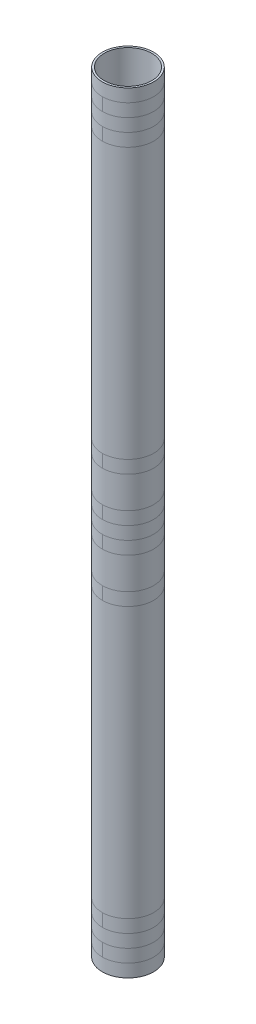
SolidWorks part; units mm, degrees
material "6063-O"
ref_plane "Front Plane" through (0, 0, 0) normal (0, 0, 1) x (1, 0, 0)
ref_plane "Top Plane" through (0, 0, 0) normal (0, 1, 0) x (1, 0, 0)
ref_plane "Right Plane" through (0, 0, 0) normal (1, 0, 0) x (0, 0, -1)
sketch "Sketch1" plane through (0, 0, 0) normal (0, 1, 0) x (1, 0, 0)
  circle A0 centre (0, 0) radius 20
  dimension "D1" = 30
extrude "Boss-Extrude1" add sketch "Sketch1" along normal blind 600
sketch "Sketch5" plane through (0, 600, 0) normal (0, 1, 0) x (1, 0, 0)
  circle A0 centre (0, 0) radius 18.5
  dimension "D1" = 24
extrude "Cut-Extrude1" cut sketch "Sketch5" against normal blind 600
ref_plane "Plane1" through (30, 0, 0) normal (1, 0, 0) x (0, 0, -1)
sketch "Sketch6" plane through (30, 0, 0) normal (1, 0, 0) x (0, 0, -1)
  line L0 (-20, 0) -> (20, 0) construction
  line L1 (-20, 600) -> (-20, 0) construction
  circle A0 centre (-5, 279.5) radius 2.5
  circle A1 centre (-5, 325.5) radius 2.5
  circle A2 centre (20, 300) radius 2.5
  dimension "D1" = 279.5
  dimension "D3" = 15
  dimension "D4" = 40
  dimension "D5" = 46
  dimension "D6" = 300
  dimension "D2" = 15
sketch "Sketch10" plane through (30, 0, 0) normal (1, 0, 0) x (0, 0, -1)
  line L0 (-20, 10) -> (20, 10)
  line L1 (-20, 600) -> (-20, 0) construction
  line L2 (20, 0) -> (20, 600) construction
  line L3 (20, 10) -> (20, 20)
  line L4 (20, 20) -> (-20, 20)
  line L5 (-20, 20) -> (-20, 10)
  line L6 (-20, 590) -> (20, 590)
  line L7 (20, 590) -> (20, 580)
  line L8 (20, 580) -> (-20, 580)
  line L9 (-20, 580) -> (-20, 590)
  line L10 (-20, 570) -> (20, 570)
  line L11 (20, 570) -> (20, 560)
  line L12 (20, 560) -> (-20, 560)
  line L13 (-20, 560) -> (-20, 570)
  line L14 (-20, 30) -> (-20, 40)
  line L15 (-20, 40) -> (20, 40)
  line L16 (20, 40) -> (20, 30)
  line L17 (20, 30) -> (-20, 30)
  line L18 (-20, 0) -> (20, 0) construction
  line L19 (20, 600) -> (-20, 600) construction
  line L20 (-20, 295) -> (20, 295)
  line L21 (20, 295) -> (20, 285)
  line L22 (20, 285) -> (-20, 285)
  line L23 (-20, 285) -> (-20, 295)
  line L24 (-20, 315) -> (20, 315)
  line L25 (20, 315) -> (20, 305)
  line L26 (20, 305) -> (-20, 305)
  line L27 (-20, 305) -> (-20, 315)
  dimension "D1" = 10
  dimension "D2" = 10
  dimension "D3" = 10
  dimension "D4" = 10
  dimension "D5" = 10
  dimension "D6" = 10
  dimension "D7" = 10
  dimension "D8" = 10
  dimension "D9" = 10
  dimension "D10" = 10
  dimension "D11" = 10
split line "Split Line2"
sketch "Sketch11" plane through (30, 0, 0) normal (1, 0, 0) x (0, 0, -1)
  line L0 (-20, 349.58) -> (-20, 339.58)
  line L1 (-20, 560) -> (-20, 315) construction
  line L2 (-20, 260.42) -> (-20, 250.42)
  line L3 (-20, 285) -> (-20, 40) construction
  line L4 (-20, 285) -> (20, 285) construction
  line L5 (20, 315) -> (-20, 315) construction
  line L6 (-20, 349.58) -> (0, 349.58)
  line L8 (0, 339.58) -> (-20, 339.58)
  line L9 (-20, 260.42) -> (0, 260.42)
  line L11 (0, 250.42) -> (-20, 250.42)
  line L12 (0, 349.58) -> (20, 349.58)
  line L13 (20, 315) -> (20, 560) construction
  line L14 (20, 349.58) -> (20, 339.58)
  line L15 (20, 339.58) -> (0, 339.58)
  line L16 (0, 260.42) -> (20, 260.42)
  line L17 (20, 40) -> (20, 285) construction
  line L18 (20, 260.42) -> (20, 250.42)
  line L19 (20, 250.42) -> (0, 250.42)
  dimension "D1" = 24.58
  dimension "D2" = 10
  dimension "D3" = 24.58
  dimension "D4" = 10
split line "Split Line6"
ref_plane "Plane2" through (0, 0, 30) normal (0, 0, 1) x (1, 0, 0)
sketch "Sketch9" plane through (0, 0, 30) normal (0, 0, 1) x (1, 0, 0)
  line L0 (-17.7777, 586.4464) -> (17.9432, 586.4464)
  line L1 (17.9432, 586.4464) -> (17.9432, 538.4114)
  line L2 (17.9432, 538.4114) -> (-17.7777, 538.4114)
  line L3 (-17.7777, 538.4114) -> (-17.7777, 586.4464)
  line L4 (-17.7777, 10.5086) -> (17.9432, 10.5086)
  line L5 (17.9432, 10.5086) -> (17.9432, 58.7449)
  line L6 (17.9432, 58.7449) -> (-17.7777, 58.7449)
  line L7 (-17.7777, 58.7449) -> (-17.7777, 10.5086)
  circle A0 centre (-7.8259, 575.72) radius 2.5
  circle A1 centre (7.9699, 575.72) radius 2.5
  circle A2 centre (-7.8259, 559.1861) radius 2.5
  circle A3 centre (7.9699, 559.1861) radius 2.5
  circle A4 centre (-7.8259, 45.6469) radius 2.5
  circle A5 centre (7.9699, 45.6469) radius 2.5
  circle A6 centre (7.9699, 28.7529) radius 2.5
  circle A7 centre (-7.8259, 28.7529) radius 2.5
